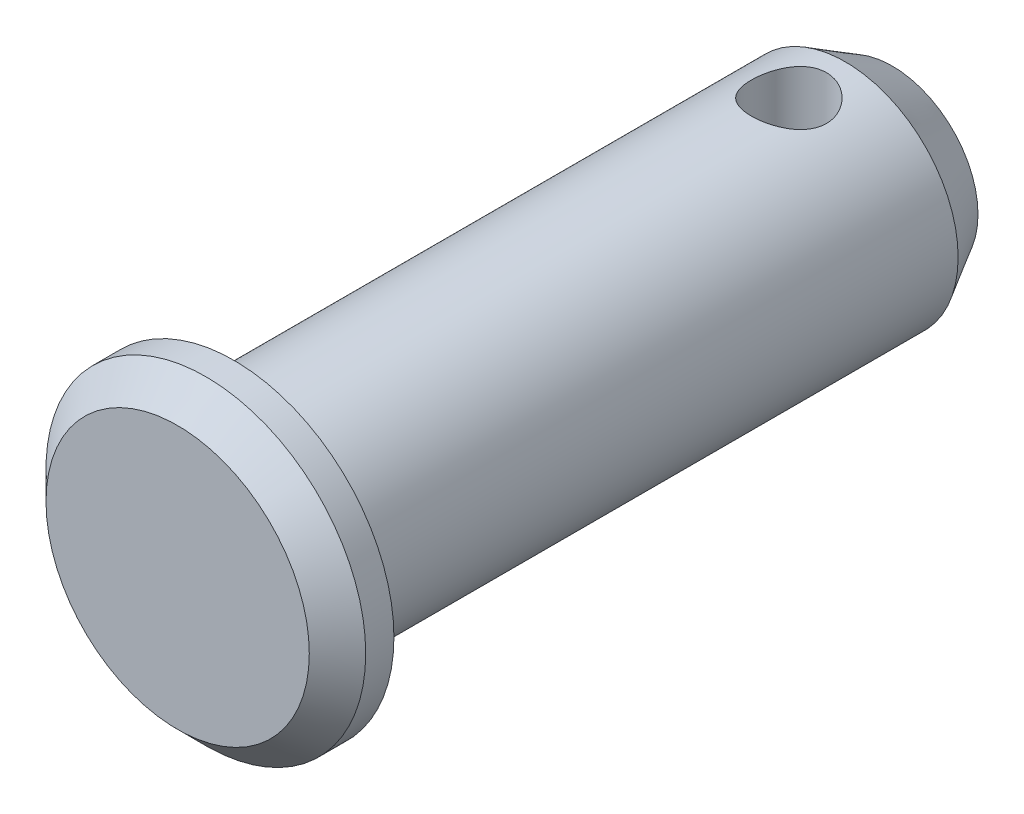
SolidWorks part; units mm, degrees
material "1.0545 (S355N)"
ref_plane "Płaszczyzna przednia" through (0, 0, 0) normal (0, 0, 1) x (1, 0, 0)
ref_plane "Płaszczyzna górna" through (0, 0, 0) normal (0, 1, 0) x (1, 0, 0)
ref_plane "Płaszczyzna prawa" through (0, 0, 0) normal (1, 0, 0) x (0, 0, -1)
sketch "Szkic1" plane through (0, 0, 0) normal (0, 1, 0) x (1, 0, 0)
  line L0 (7, -19) -> (-7, -19)
  line L1 (-8.5, -17.5) -> (-8.5, -16)
  line L2 (-8.5, -16) -> (-6, -16)
  line L3 (-6, -16) -> (-6, 16.5)
  line L4 (-4.5566, 19) -> (4.5566, 19)
  line L5 (6, 16.5) -> (6, -16)
  line L6 (6, -16) -> (8.5, -16)
  line L7 (8.5, -16) -> (8.5, -17.5)
  line L8 (8.5, -17.5) -> (7, -19)
  line L9 (-7, -19) -> (-8.5, -17.5)
  line L10 (4.5566, 19) -> (6, 16.5)
  line L11 (-6, 16.5) -> (-4.5566, 19)
  line L12 (0, -19) -> (0, 19)
  point P0 (8.5, -19)
  point P1 (-8.5, -19)
  point P5 (-6, 19)
  point P6 (6, 19)
  point P7 (0, 0)
  point P17 (0, 19)
  point P19 (0, -19)
  dimension "D1" = 17
  dimension "D2" = 12
  dimension "D3" = 2.5
  dimension "D4" = 30
  dimension "D8" = 30
  dimension "D9" = 35
  dimension "D10" = 3
revolve "Obrót1" add sketch "Szkic1" angle 360 about L12
sketch "Szkic2" plane through (0, 0, 0) normal (0, 1, 0) x (1, 0, 0)
  line L0 (6, -16) -> (-6, -16) construction
  circle A0 centre (0, 13.5) radius 2
  dimension "D2" = 4
  dimension "D1" = 29.5
extrude "Wytnij-wyciągnięcie1" cut sketch "Szkic2" against normal through all both and the other way through all contours A0
